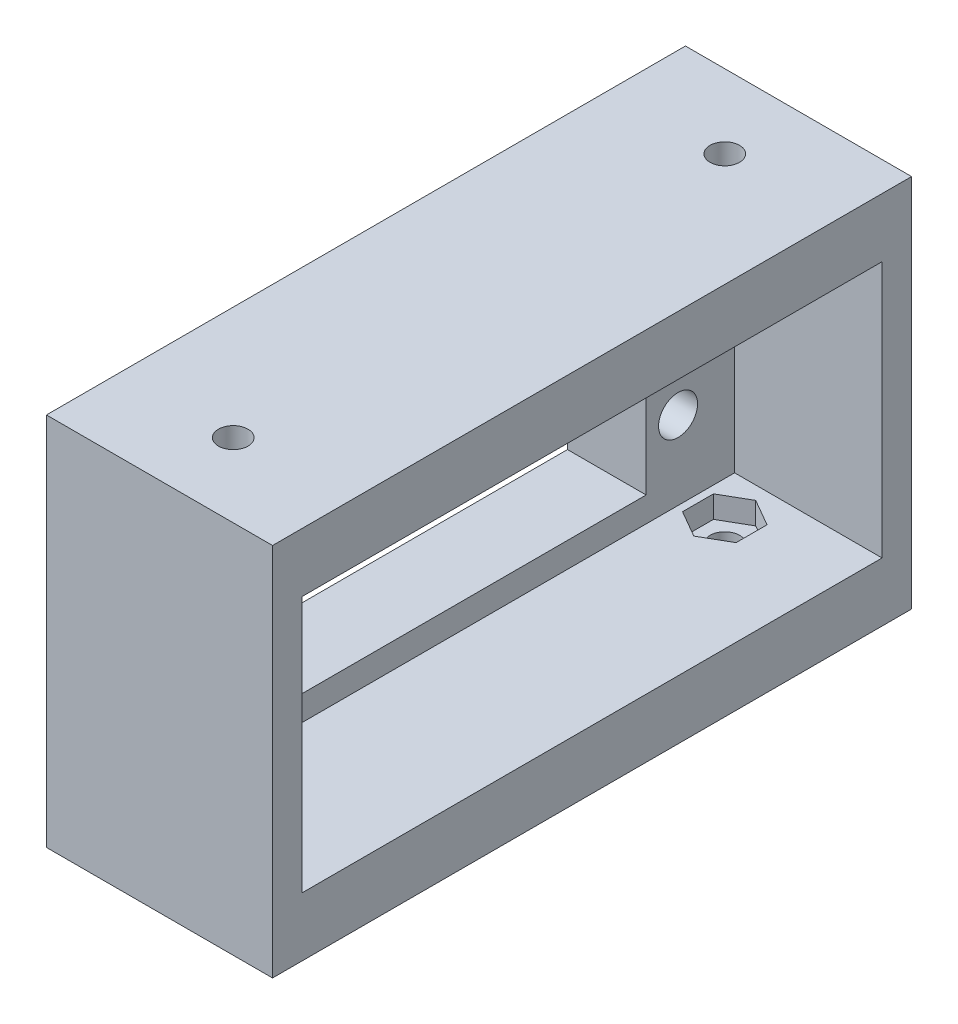
SolidWorks part; units mm, degrees
material "Custom Plastic"
ref_plane "Front Plane" through (0, 0, 0) normal (0, 0, 1) x (1, 0, 0)
ref_plane "Top Plane" through (0, 0, 0) normal (0, 1, 0) x (1, 0, 0)
ref_plane "Right Plane" through (0, 0, 0) normal (1, 0, 0) x (0, 0, -1)
sketch "Sketch1" plane through (0, 0, 0) normal (1, 0, 0) x (0, 0, -1)
  line L0 (-20.5, 10.5) -> (20.5, 10.5)
  line L1 (-20.5, 10.5) -> (-20.5, -10.5)
  line L2 (-20.5, -10.5) -> (20.5, -10.5)
  line L3 (20.5, 10.5) -> (20.5, -10.5)
  line L5 (-32.5, 19.05) -> (32.5, 19.05)
  line L6 (-32.5, 19.05) -> (-32.5, -19.05)
  line L7 (-32.5, -19.05) -> (32.5, -19.05)
  line L8 (32.5, 19.05) -> (32.5, -19.05)
  point P4 (0, 10.5)
  point P6 (20.5, 0)
  point P11 (0, 19.05)
  point P12 (32.5, 0)
  dimension "D1" = 41
  dimension "D2" = 21
  dimension "D3" = 12
  dimension "D4" = 19.05
extrude "Boss-Extrude1" add sketch "Sketch1" along normal blind 8
sketch "Sketch2" plane through (8, 0, 0) normal (1, 0, 0) x (0, 0, -1)
  line L1 (-32.5, 19.05) -> (32.5, 19.05)
  line L2 (-32.5, 19.05) -> (-32.5, -19.05)
  line L3 (-32.5, -19.05) -> (32.5, -19.05)
  line L4 (32.5, 19.05) -> (32.5, -19.05)
  line L5 (-29.5, 13.05) -> (29.5, 13.05)
  line L6 (-29.5, 13.05) -> (-29.5, -13.05)
  line L7 (-29.5, -13.05) -> (29.5, -13.05)
  line L8 (29.5, 13.05) -> (29.5, -13.05)
  point P10 (0, -13.05)
  point P12 (-29.5, 0)
  dimension "D1" = 6
  dimension "D2" = 3
extrude "Boss-Extrude2" add sketch "Sketch2" along normal blind 15
hole_wizard "5/32 (0.15625) Diameter Hole1" positions "Sketch3" profile "Sketch4" hole size "5/32" standard "ANSI Inch" end condition through all
sketch "Sketch3" plane through (0, 0, 0) normal (-1, 0, 0) x (0, 0, 1)
  line L0 (23.749, 5.08) -> (23.749, -5.08) construction
  line L1 (23.749, -5.08) -> (-23.749, -5.08) construction
  line L2 (-23.749, -5.08) -> (-23.749, 5.08) construction
  line L3 (-23.749, 5.08) -> (23.749, 5.08) construction
  point P0 (-23.6085, 5.1229)
  point P2 (-23.749, -5.08)
  point P4 (23.749, -5.08)
  point P7 (23.749, 5.08)
sketch "Sketch4" plane through (0, 5.1229, -23.6085) normal (0, 1, 0) x (0, 0, 1)
  line L0 (0, 0) -> (0, 23)
  line L1 (0, 23) -> (1.9844, 23)
  line L2 (1.9844, 23) -> (1.9844, 0)
  line L5 (1.9844, 0) -> (0, 0)
  line L11 (0, -6.35) -> (0, 107.95) construction
  dimension "Thru Hole Dia." = 3.9688
  dimension "Thru Hole Depth" = 23
hole_wizard "Ø3.0mm Dowel Hole1" positions "Sketch5" profile "Sketch6" hole size "Ø3.0" standard "ANSI Metric"
sketch "Sketch5" plane through (0, -13.05, 0) normal (0, 1, 0) x (1, 0, 0)
  line L0 (11.5, 25) -> (11.5, -25) construction
  line L2 (0, 0) -> (23, 0) construction
  line L3 (0, 32.5) -> (0, -32.5) construction
  line L4 (23, 32.5) -> (23, -32.5) construction
  point P0 (11.5, 25)
  point P2 (11.5, -25)
  point P15 (11.5, 0)
  point P17 (11.5, 0)
  dimension "D1" = 50
sketch "Sketch6" plane through (11.5, -13.05, -25) normal (1, 0, 0) x (0, 0, 1)
  line L0 (0, 0) -> (0, 6)
  line L1 (0, 6) -> (1.5, 6)
  line L2 (1.5, 6) -> (1.5, 0)
  line L5 (1.5, 0) -> (0, 0)
  line L11 (0, -6.35) -> (0, 107.95) construction
  dimension "Thru Hole Dia." = 3
  dimension "Thru Hole Depth" = 6
mirror "Mirror1" about plane through (0, 0, 0) normal (0, 1, 0) of "Ø3.0mm Dowel Hole1"
sketch "Sketch7" plane through (0, -13.05, 0) normal (0, 1, 0) x (1, 0, 0)
  line L0 (0, 32.5) -> (0, -32.5) construction
  line L1 (8.775, -26.5733) -> (11.5, -28.1466)
  line L2 (11.5, -28.1466) -> (14.225, -26.5733)
  line L3 (14.225, -26.5733) -> (14.225, -23.4267)
  line L4 (14.225, -23.4267) -> (11.5, -21.8534)
  line L5 (11.5, -21.8534) -> (8.775, -23.4267)
  line L6 (8.775, -23.4267) -> (8.775, -26.5733)
  circle A0 centre (11.5, -25) radius 2.725 construction
  dimension "D1" = 5.45
extrude "Cut-Extrude1" cut sketch "Sketch7" against normal blind 2.25
mirror "Mirror2" about plane through (0, 0, 0) normal (0, 1, 0) of "Cut-Extrude1" second plane through (0, 0, 0) second plane normal (0, 0, 1)
sketch "Sketch9" plane through (0, 0, 0) normal (-1, 0, 0) x (0, 0, 1)
  line L0 (-20.5, -10.5) -> (-20.5, 10.5) construction
  line L1 (-20.5, -1) -> (-26.5, -1)
  line L2 (-20.5, -1) -> (-20.5, 1)
  line L3 (-20.5, 1) -> (-26.5, 1)
  line L4 (-26.5, -1) -> (-26.5, 1)
  line L5 (20.5, 10.5) -> (20.5, -10.5) construction
  line L6 (20.5, -1) -> (26.5, -1)
  line L7 (20.5, -1) -> (20.5, 1)
  line L8 (20.5, 1) -> (26.5, 1)
  line L9 (26.5, -1) -> (26.5, 1)
  point P13 (-26.5, 0)
  point P15 (26.5, 0)
  dimension "D1" = 2
  dimension "D2" = 6
extrude "Cut-Extrude2" cut sketch "Sketch9" against normal up to surface (8 mm away) up to face at (8, 5.1229, -25.5929)
